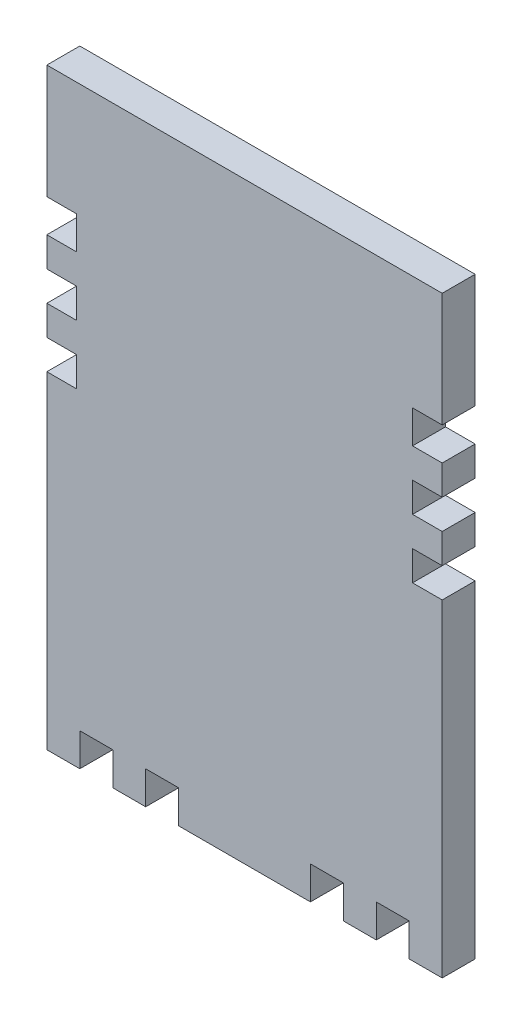
SolidWorks part; units mm, degrees
ref_plane "Plan de face" through (0, 0, 0) normal (0, 0, 1) x (1, 0, 0)
ref_plane "Plan de dessus" through (0, 0, 0) normal (0, 1, 0) x (1, 0, 0)
ref_plane "Plan de droite" through (0, 0, 0) normal (1, 0, 0) x (0, 0, -1)
sketch "Esquisse2" plane through (0, 0, 0) normal (0, 0, 1) x (1, 0, 0)
  line L27 (28.1523, 124.2724) -> (28.1523, 74.5819)
  line L28 (28.1523, 124.2724) -> (32.6523, 124.2724)
  line L29 (32.6523, 124.2724) -> (32.6523, 128.7724)
  line L30 (32.6523, 128.7724) -> (28.1523, 128.7724)
  line L31 (28.1523, 128.7724) -> (28.1523, 133.2724)
  line L32 (32.6523, 133.2724) -> (28.1523, 133.2724)
  line L33 (32.6523, 133.2724) -> (32.6523, 137.7724)
  line L34 (32.6523, 137.7724) -> (28.1523, 137.7724)
  line L35 (28.1523, 137.7724) -> (28.1523, 142.2724)
  line L36 (28.1523, 142.2724) -> (32.6523, 142.2724)
  line L37 (32.6523, 142.2724) -> (32.6523, 147.2724)
  line L38 (32.6523, 147.2724) -> (28.1523, 147.2724)
  line L59 (28.1523, 164.5819) -> (28.1523, 147.2724)
  line L61 (28.1523, 164.5819) -> (88.1523, 164.5819)
  line L62 (58.1523, 164.5819) -> (58.1523, 74.5819)
  line L64 (88.1523, 164.5819) -> (88.1523, 147.2724)
  line L65 (83.6523, 147.2724) -> (88.1523, 147.2724)
  line L66 (83.6523, 142.2724) -> (83.6523, 147.2724)
  line L67 (88.1523, 142.2724) -> (83.6523, 142.2724)
  line L68 (88.1523, 137.7724) -> (88.1523, 142.2724)
  line L69 (83.6523, 137.7724) -> (88.1523, 137.7724)
  line L70 (83.6523, 133.2724) -> (83.6523, 137.7724)
  line L71 (83.6523, 133.2724) -> (88.1523, 133.2724)
  line L72 (88.1523, 128.7724) -> (88.1523, 133.2724)
  line L73 (83.6523, 128.7724) -> (88.1523, 128.7724)
  line L74 (83.6523, 124.2724) -> (83.6523, 128.7724)
  line L75 (88.1523, 124.2724) -> (83.6523, 124.2724)
  line L76 (88.1523, 124.2724) -> (88.1523, 74.5819)
  line L77 (33.1523, 74.5819) -> (33.1523, 79.5819)
  line L78 (33.1523, 79.5819) -> (38.1523, 79.5819)
  line L79 (38.1523, 79.5819) -> (38.1523, 74.5819)
  line L80 (38.1523, 74.5819) -> (43.1523, 74.5819)
  line L81 (43.1523, 74.5819) -> (43.1523, 79.5819)
  line L82 (43.1523, 79.5819) -> (48.1523, 79.5819)
  line L83 (48.1523, 79.5819) -> (48.1523, 74.5819)
  line L84 (28.1523, 74.5819) -> (33.1523, 74.5819)
  line L85 (83.1523, 74.5819) -> (83.1523, 79.5819)
  line L86 (83.1523, 79.5819) -> (78.1523, 79.5819)
  line L87 (78.1523, 79.5819) -> (78.1523, 74.5819)
  line L88 (83.1523, 74.5819) -> (88.1523, 74.5819)
  line L89 (73.1523, 74.5819) -> (73.1523, 79.5819)
  line L90 (73.1523, 79.5819) -> (68.1523, 79.5819)
  line L91 (68.1523, 79.5819) -> (68.1523, 74.5819)
  line L92 (48.1523, 74.5819) -> (68.1523, 74.5819)
  line L93 (73.1523, 74.5819) -> (78.1523, 74.5819)
  point P26 (30.4023, 128.7724)
  point P27 (30.4023, 133.2724)
  point P28 (30.4023, 147.2724)
  dimension "D3" = 5
  dimension "D1" = 17.3094
  dimension "D4" = 30
  dimension "D5" = 90
  dimension "D6" = 4.5
  dimension "D7" = 4.5
  dimension "D8" = 30
  dimension "D9" = 4.5
  dimension "D10" = 5
  dimension "D11" = 5
  dimension "D12" = 4.5
  dimension "D13" = 4.5
  dimension "D14" = 5
  dimension "D15" = 5
  dimension "D16" = 5
  dimension "D17" = 4.5
  dimension "D18" = 4.5
  dimension "D19" = 4.5
  dimension "D20" = 4.5
  dimension "D21" = 4.5
  dimension "D22" = 4.5
  dimension "D23" = 5
  dimension "D24" = 15
  dimension "D25" = 4.5
  dimension "D26" = 4.5
  dimension "D27" = 5
  dimension "D28" = 4.5
  dimension "D29" = 4.5
  dimension "D30" = 4.5
extrude "Boss.-Extru.1" add sketch "Esquisse2" along normal blind 5 contours L89 L93 L87 L86 L85 L88 L76 L75 L74 L73 L72 L71 L70 L69 L68 L67 L66 L65 L64 L61 L62 L92 L91 L90 | L83 L92 L62 L61 L59 L38 L37 L36 L35 L34 L33 L32 L31 L30 L29 L28 L27 L84 L77 L78 L79 L80 L81 L82
